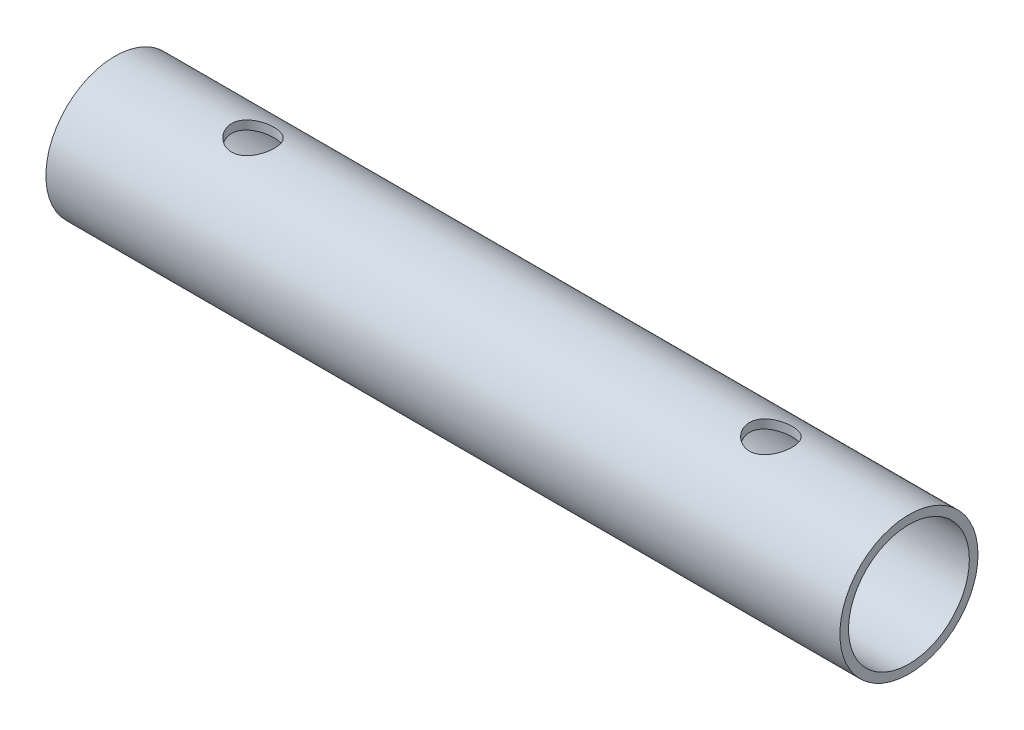
SolidWorks part; units mm, degrees
ref_plane "Front" through (0, 0, 0) normal (0, 0, 1) x (1, 0, 0)
ref_plane "Top" through (0, 0, 0) normal (0, 1, 0) x (1, 0, 0)
ref_plane "Right" through (0, 0, 0) normal (1, 0, 0) x (0, 0, -1)
sketch "草图1" plane through (0, 0, 0) normal (1, 0, 0) x (0, 0, -1)
  circle A0 centre (0, 0) radius 8.75
  circle A1 centre (0, 0) radius 10
extrude "凸台-拉伸1" add sketch "草图1" along normal blind 115
sketch "草图2" plane through (0, 0, 0) normal (0, 1, 0) x (1, 0, 0)
  line L0 (0, 0) -> (20, 0) construction
  line L1 (0, 0) -> (95, 0) construction
  circle A0 centre (20, 0) radius 3.1
  circle A1 centre (95, 0) radius 3.1
extrude "切除-拉伸1" cut sketch "草图2" against normal through all both and the other way through all
